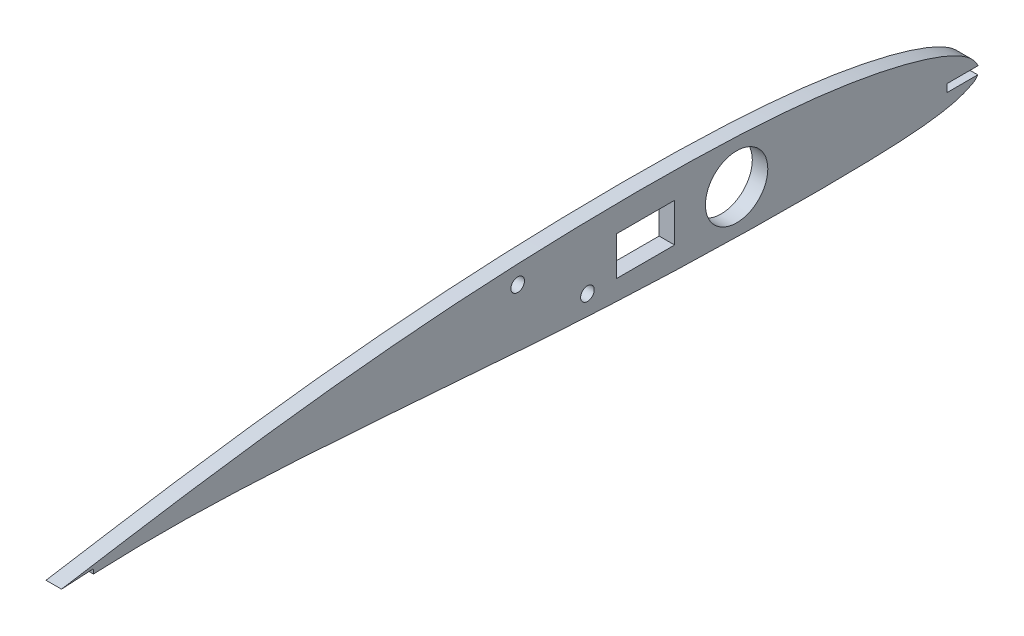
SolidWorks part; units mm, degrees
material "ABS generico"
ref_plane "Piano frontale" through (0, 0, 0) normal (0, 0, 1) x (1, 0, 0)
ref_plane "Piano superiore" through (0, 0, 0) normal (0, 1, 0) x (1, 0, 0)
ref_plane "Piano destro" through (0, 0, 0) normal (1, 0, 0) x (0, 0, -1)
curve "Curva1"
  spline degree 3 poles (0, 0.1724, 248.285) (0, -0.053, 250.4273) (0, 0.2462, 248.3284) (0, 0.5529, 246.6445) (0, 1.2459, 242.6221) (0, 2.0989, 237.7464) (0, 3.1818, 231.3634) (0, 4.2933, 223.9772) (0, 5.7312, 215.5604) (0, 7.1315, 206.3004) (0, 8.6324, 196.1631) (0, 10.1162, 185.3524) (0, 11.5493, 173.9891) (0, 12.8816, 162.1914) (0, 14.0593, 150.0724) (0, 15.0523, 137.7438) (0, 15.8256, 125.3116) (0, 16.3834, 112.8888) (0, 16.7267, 100.597) (0, 16.8648, 88.5669) (0, 16.792, 76.9314) (0, 16.4941, 65.8165) (0, 15.9609, 55.3329) (0, 15.1594, 45.573) (0, 14.0978, 36.6074) (0, 12.7884, 28.4972) (0, 11.2839, 21.2988) (0, 9.6413, 15.0749) (0, 7.9136, 9.8809) (0, 6.1182, 5.7699) (0, 4.2384, 2.7289) (0, 2.3057, 0.8126) (0, 0.7927, 0.0312) (0, -0.4105, -0.0213) (0, -1.7115, 0.4949) (0, -2.8658, 2.6253) (0, -4.0404, 5.6977) (0, -4.9287, 10.0719) (0, -5.5974, 15.6262) (0, -6.0122, 22.4122) (0, -6.265, 30.3619) (0, -6.3814, 39.3972) (0, -6.3554, 49.3987) (0, -6.2185, 60.2453) (0, -5.9476, 71.8018) (0, -5.5368, 83.9408) (0, -4.9386, 96.5461) (0, -4.1527, 109.5201) (0, -3.2196, 122.7671) (0, -2.1909, 136.1764) (0, -1.148, 149.6158) (0, -0.1602, 162.9314) (0, 0.706, 175.9537) (0, 1.3896, 188.4999) (0, 1.8332, 200.3712) (0, 1.9676, 211.3376) (0, 1.8232, 221.1842) (0, 1.4973, 229.6804) (0, 1.0741, 236.8065) (0, 0.6857, 242.1894) (0, 0.3087, 246.5181) (0, 0.1724, 248.285) (0, -0.053, 250.4273) (0, 0.2462, 248.3284) knots -0.014202 -0.006329 -0.001589 0 0.001576 0.006211 0.01368 0.023764 0.036307 0.051658 0.068045 0.086769 0.107053 0.128647 0.151303 0.174786 0.19886 0.223309 0.247929 0.272522 0.296848 0.320648 0.343669 0.365658 0.3864 0.405741 0.423561 0.439779 0.454311 0.467034 0.477831 0.486643 0.493542 0.498786 0.50271 0.50309 0.505896 0.510322 0.516831 0.525521 0.536535 0.549945 0.565696 0.583577 0.603379 0.624844 0.647727 0.671743 0.696673 0.722357 0.748609 0.77521 0.801891 0.828329 0.854175 0.879074 0.902636 0.924421 0.943939 0.960827 0.974827 0.985798 0.993671 0.998411 1 1.001576 1.006211 1.01368 periodic
sketch "Schizzo1" plane through (0, 0, 0) normal (1, 0, 0) x (0, 0, -1)
  line L0 (-250, 0) -> (0.0001, 0.0174) construction
  line L1 (0.0001, 0.0174) -> (-0.0034, 50.0174) construction
  line L2 (-62.4999, 16.3096) -> (-62.4999, -6.155) construction
  line L4 (-78.4999, 10.0773) -> (-93.4999, 10.0773)
  line L5 (-78.4999, 10.0773) -> (-78.4999, 0.0773)
  line L6 (-78.4999, 0.0773) -> (-93.4999, 0.0773)
  line L7 (-93.4999, 10.0773) -> (-93.4999, 0.0773)
  circle A0 centre (-62.4999, 5.0773) radius 8.05
  spline S0 degree 3 poles (-248.3284, 0.2462) (-250.4273, -0.053) (-248.285, 0.1724) (-246.5181, 0.3087) (-242.1894, 0.6857) (-236.8065, 1.0741) (-229.6804, 1.4973) (-221.1842, 1.8232) (-211.3376, 1.9676) (-200.3712, 1.8332) (-188.4999, 1.3896) (-175.9537, 0.706) (-162.9314, -0.1602) (-149.6158, -1.148) (-136.1764, -2.1909) (-122.7671, -3.2196) (-109.5201, -4.1527) (-96.5461, -4.9386) (-83.9408, -5.5368) (-71.8018, -5.9476) (-60.2453, -6.2185) (-49.3987, -6.3554) (-39.3972, -6.3814) (-30.3619, -6.265) (-22.4122, -6.0122) (-15.6262, -5.5974) (-10.0719, -4.9287) (-5.6977, -4.0404) (-2.6253, -2.8658) (-0.4949, -1.7115) (0.0213, -0.4105) (-0.0312, 0.7927) (-0.8126, 2.3057) (-2.7289, 4.2384) (-5.7699, 6.1182) (-9.8809, 7.9136) (-15.0749, 9.6413) (-21.2988, 11.2839) (-28.4972, 12.7884) (-36.6074, 14.0978) (-45.573, 15.1594) (-55.3329, 15.9609) (-65.8165, 16.4941) (-76.9314, 16.792) (-88.5669, 16.8648) (-100.597, 16.7267) (-112.8888, 16.3834) (-125.3116, 15.8256) (-137.7438, 15.0523) (-150.0724, 14.0593) (-162.1914, 12.8816) (-173.9891, 11.5493) (-185.3524, 10.1162) (-196.1631, 8.6324) (-206.3004, 7.1315) (-215.5604, 5.7312) (-223.9772, 4.2933) (-231.3634, 3.1818) (-237.7464, 2.0989) (-242.6221, 1.2459) (-246.6445, 0.5529) (-248.3284, 0.2462) (-250.4273, -0.053) (-248.285, 0.1724) knots -0.01368 -0.006211 -0.001576 0 0.001589 0.006329 0.014202 0.025173 0.039173 0.056061 0.075579 0.097364 0.120926 0.145825 0.171671 0.198109 0.22479 0.251391 0.277643 0.303327 0.328257 0.352273 0.375156 0.396621 0.416423 0.434304 0.450055 0.463465 0.474479 0.483169 0.489678 0.494104 0.49691 0.49729 0.501214 0.506458 0.513357 0.522169 0.532966 0.545689 0.560221 0.576439 0.594259 0.6136 0.634342 0.656331 0.679352 0.703152 0.727478 0.752071 0.776691 0.80114 0.825214 0.848697 0.871353 0.892947 0.913231 0.931955 0.948342 0.963693 0.976236 0.98632 0.993789 0.998424 1 1.001589 1.006329 1.014202 only from (-250, 0) to (-250, 0) construction
  spline S1 degree 3 poles (-248.3284, 0.2462) (-250.4273, -0.053) (-248.285, 0.1724) (-246.5181, 0.3087) (-242.1894, 0.6857) (-236.8065, 1.0741) (-229.6804, 1.4973) (-221.1842, 1.8232) (-211.3376, 1.9676) (-200.3712, 1.8332) (-188.4999, 1.3896) (-175.9537, 0.706) (-162.9314, -0.1602) (-149.6158, -1.148) (-136.1764, -2.1909) (-122.7671, -3.2196) (-109.5201, -4.1527) (-96.5461, -4.9386) (-83.9408, -5.5368) (-71.8018, -5.9476) (-60.2453, -6.2185) (-49.3987, -6.3554) (-39.3972, -6.3814) (-30.3619, -6.265) (-22.4122, -6.0122) (-15.6262, -5.5974) (-10.0719, -4.9287) (-5.6977, -4.0404) (-2.6253, -2.8658) (-0.4949, -1.7115) (0.0213, -0.4105) (-0.0312, 0.7927) (-0.8126, 2.3057) (-2.7289, 4.2384) (-5.7699, 6.1182) (-9.8809, 7.9136) (-15.0749, 9.6413) (-21.2988, 11.2839) (-28.4972, 12.7884) (-36.6074, 14.0978) (-45.573, 15.1594) (-55.3329, 15.9609) (-65.8165, 16.4941) (-76.9314, 16.792) (-88.5669, 16.8648) (-100.597, 16.7267) (-112.8888, 16.3834) (-125.3116, 15.8256) (-137.7438, 15.0523) (-150.0724, 14.0593) (-162.1914, 12.8816) (-173.9891, 11.5493) (-185.3524, 10.1162) (-196.1631, 8.6324) (-206.3004, 7.1315) (-215.5604, 5.7312) (-223.9772, 4.2933) (-231.3634, 3.1818) (-237.7464, 2.0989) (-242.6221, 1.2459) (-246.6445, 0.5529) (-248.3284, 0.2462) (-250.4273, -0.053) (-248.285, 0.1724) knots -0.01368 -0.006211 -0.001576 0 0.001589 0.006329 0.014202 0.025173 0.039173 0.056061 0.075579 0.097364 0.120926 0.145825 0.171671 0.198109 0.22479 0.251391 0.277643 0.303327 0.328257 0.352273 0.375156 0.396621 0.416423 0.434304 0.450055 0.463465 0.474479 0.483169 0.489678 0.494104 0.49691 0.49729 0.501214 0.506458 0.513357 0.522169 0.532966 0.545689 0.560221 0.576439 0.594259 0.6136 0.634342 0.656331 0.679352 0.703152 0.727478 0.752071 0.776691 0.80114 0.825214 0.848697 0.871353 0.892947 0.913231 0.931955 0.948342 0.963693 0.976236 0.98632 0.993789 0.998424 1 1.001589 1.006329 1.014202 only from (-250, 0) to (-250, 0)
  point P11 (-78.4999, 5.0773)
  dimension "D3" = 16.1
  dimension "D1" = 50
  dimension "D2" = 62.5
  dimension "D4" = 15
  dimension "D5" = 10
  dimension "D6" = 16
extrude "CorpoFoam" add sketch "Schizzo1" along normal blind 4
sketch "Schizzo2" plane through (0, 0, 0) normal (-1, 0, 0) x (0, 0, 1)
  line L0 (0, 0) -> (62.4999, 5.0773) construction
  line L9 (-0.0001, 1) -> (8.1999, 1)
  line L13 (-0.0001, 1) -> (-0.0001, -1)
  line L14 (-0.0001, -1) -> (8.1999, -1)
  line L15 (8.1999, 1) -> (8.1999, -1)
  spline S1 degree 3 poles (248.285, 0.1724) (250.4273, -0.053) (248.3284, 0.2462) (246.6445, 0.5529) (242.6221, 1.2459) (237.7464, 2.0989) (231.3634, 3.1818) (223.9772, 4.2933) (215.5604, 5.7312) (206.3004, 7.1315) (196.1631, 8.6324) (185.3524, 10.1162) (173.9891, 11.5493) (162.1914, 12.8816) (150.0724, 14.0593) (137.7438, 15.0523) (125.3116, 15.8256) (112.8888, 16.3834) (100.597, 16.7267) (88.5669, 16.8648) (76.9314, 16.792) (65.8165, 16.4941) (55.3329, 15.9609) (45.573, 15.1594) (36.6074, 14.0978) (28.4972, 12.7884) (21.2988, 11.2839) (15.0749, 9.6413) (9.8809, 7.9136) (5.7699, 6.1182) (2.7289, 4.2384) (0.8126, 2.3057) (0.0312, 0.7927) (-0.0213, -0.4105) (0.4949, -1.7115) (2.6253, -2.8658) (5.6977, -4.0404) (10.0719, -4.9287) (15.6262, -5.5974) (22.4122, -6.0122) (30.3619, -6.265) (39.3972, -6.3814) (49.3987, -6.3554) (60.2453, -6.2185) (71.8018, -5.9476) (83.9408, -5.5368) (96.5461, -4.9386) (109.5201, -4.1527) (122.7671, -3.2196) (136.1764, -2.1909) (149.6158, -1.148) (162.9314, -0.1602) (175.9537, 0.706) (188.4999, 1.3896) (200.3712, 1.8332) (211.3376, 1.9676) (221.1842, 1.8232) (229.6804, 1.4973) (236.8065, 1.0741) (242.1894, 0.6857) (246.5181, 0.3087) (248.285, 0.1724) (250.4273, -0.053) (248.3284, 0.2462) knots -0.014202 -0.006329 -0.001589 0 0.001576 0.006211 0.01368 0.023764 0.036307 0.051658 0.068045 0.086769 0.107053 0.128647 0.151303 0.174786 0.19886 0.223309 0.247929 0.272522 0.296848 0.320648 0.343669 0.365658 0.3864 0.405741 0.423561 0.439779 0.454311 0.467034 0.477831 0.486643 0.493542 0.498786 0.50271 0.50309 0.505896 0.510322 0.516831 0.525521 0.536535 0.549945 0.565696 0.583577 0.603379 0.624844 0.647727 0.671743 0.696673 0.722357 0.748609 0.77521 0.801891 0.828329 0.854175 0.879074 0.902636 0.924421 0.943939 0.960827 0.974827 0.985798 0.993671 0.998411 1 1.001576 1.006211 1.01368 only from (250, 0) to (250, 0) construction
  point P6 (-0.0001, 0)
  dimension "D1" = 2
  dimension "D2" = 8.2
extrude "IntagliFrontali" cut sketch "Schizzo2" against normal through all
sketch "Schizzo3" plane through (0, 0, 0) normal (-1, 0, 0) x (0, 0, 1)
  line L0 (98.4999, 13.9643) -> (98.4999, 16.7316) construction
  line L1 (98.4999, 13.9643) -> (121.4999, 13.9643) construction
  line L2 (98.4999, 13.9643) -> (98.4999, -2.0357) construction
  line L3 (98.4999, -2.0357) -> (121.4999, -2.0357) construction
  line L4 (121.4999, 13.9643) -> (121.4999, -2.0357) construction
  line L5 (98.4999, -2.0357) -> (98.4999, -4.803) construction
  line L6 (93.4999, 10.0773) -> (93.4999, 0.0773) construction
  line L7 (98.4999, -2.0357) -> (100.9999, 0.4643) construction
  line L8 (100.9999, 0.4643) -> (118.9999, 11.4643) construction
  line L9 (118.9999, 11.4643) -> (121.4999, 13.9643) construction
  circle A0 centre (100.9999, 0.4643) radius 1.75
  circle A1 centre (118.9999, 11.4643) radius 1.75
  spline S0 degree 3 poles (0.2015, 1) (0.3423, 1.3625) (1.0086, 2.5034) (2.7289, 4.2384) (5.7699, 6.1182) (9.8809, 7.9136) (15.0749, 9.6413) (21.2988, 11.2839) (28.4972, 12.7884) (36.6074, 14.0978) (45.573, 15.1594) (55.3329, 15.9609) (65.8165, 16.4941) (76.9314, 16.792) (88.5669, 16.8648) (100.597, 16.7267) (112.8888, 16.3834) (125.3116, 15.8256) (137.7438, 15.0523) (150.0724, 14.0593) (162.1914, 12.8816) (173.9891, 11.5493) (185.3524, 10.1162) (196.1631, 8.6324) (206.3004, 7.1315) (215.5604, 5.7312) (223.9772, 4.2933) (231.3634, 3.1818) (237.7464, 2.0989) (242.6221, 1.2459) (246.6445, 0.5529) (248.3284, 0.2462) (250.4273, -0.053) (248.285, 0.1724) (246.5181, 0.3087) (242.1894, 0.6857) (236.8065, 1.0741) (229.6804, 1.4973) (221.1842, 1.8232) (211.3376, 1.9676) (200.3712, 1.8332) (188.4999, 1.3896) (175.9537, 0.706) (162.9314, -0.1602) (149.6158, -1.148) (136.1764, -2.1909) (122.7671, -3.2196) (109.5201, -4.1527) (96.5461, -4.9386) (83.9408, -5.5368) (71.8018, -5.9476) (60.2453, -6.2185) (49.3987, -6.3554) (39.3972, -6.3814) (30.3619, -6.265) (22.4122, -6.0122) (15.6262, -5.5974) (10.0719, -4.9287) (5.6977, -4.0404) (2.6253, -2.8658) (0.8093, -1.8819) (0.3291, -1.1192) (0.2665, -1) knots 0.498933 0.498933 0.498933 0.498933 0.501214 0.506458 0.513357 0.522169 0.532966 0.545689 0.560221 0.576439 0.594259 0.6136 0.634342 0.656331 0.679352 0.703152 0.727478 0.752071 0.776691 0.80114 0.825214 0.848697 0.871353 0.892947 0.913231 0.931955 0.948342 0.963693 0.976236 0.98632 0.993789 0.998424 1 1.001589 1.006329 1.014202 1.025173 1.039173 1.056061 1.075579 1.097364 1.120926 1.145825 1.171671 1.198109 1.22479 1.251391 1.277643 1.303327 1.328257 1.352273 1.375156 1.396621 1.416423 1.434304 1.450055 1.463465 1.474479 1.483169 1.489678 1.494104 1.494882 1.494882 1.494882 1.494882 construction
  dimension "D4" = 3.5
  dimension "D1" = 23
  dimension "D2" = 16
  dimension "D3" = 5
  dimension "D5" = 2.5
  dimension "D6" = 2.5
  dimension "D7" = 45
extrude "ForiTrasduttorePitot" cut sketch "Schizzo3" against normal through all
sketch "Schizzo4" plane through (0, 0, 0) normal (-1, 0, 0) x (0, 0, 1)
  line L0 (228.544, 2.7244) -> (228.4772, 1.5262)
  line L1 (228.4772, 1.5262) -> (236.6645, 1.07)
  line L2 (236.6645, 1.07) -> (236.7313, 2.2681)
  line L3 (236.7313, 2.2681) -> (228.544, 2.7244)
  line L4 (237.191, 10.5177) -> (236.2665, -6.0737)
  line L5 (236.2665, -6.0737) -> (255.0429, -7.12)
  line L6 (255.0429, -7.12) -> (255.9674, 9.4715)
  line L7 (255.9674, 9.4715) -> (237.191, 10.5177)
  spline S0 degree 3 poles (0.2015, 1) (0.3423, 1.3625) (1.0086, 2.5034) (2.7289, 4.2384) (5.7699, 6.1182) (9.8809, 7.9136) (15.0749, 9.6413) (21.2988, 11.2839) (28.4972, 12.7884) (36.6074, 14.0978) (45.573, 15.1594) (55.3329, 15.9609) (65.8165, 16.4941) (76.9314, 16.792) (88.5669, 16.8648) (100.597, 16.7267) (112.8888, 16.3834) (125.3116, 15.8256) (137.7438, 15.0523) (150.0724, 14.0593) (162.1914, 12.8816) (173.9891, 11.5493) (185.3524, 10.1162) (196.1631, 8.6324) (206.3004, 7.1315) (215.5604, 5.7312) (223.9772, 4.2933) (231.3634, 3.1818) (237.7464, 2.0989) (242.6221, 1.2459) (246.6445, 0.5529) (248.3284, 0.2462) (250.4273, -0.053) (248.285, 0.1724) (246.5181, 0.3087) (242.1894, 0.6857) (236.8065, 1.0741) (229.6804, 1.4973) (221.1842, 1.8232) (211.3376, 1.9676) (200.3712, 1.8332) (188.4999, 1.3896) (175.9537, 0.706) (162.9314, -0.1602) (149.6158, -1.148) (136.1764, -2.1909) (122.7671, -3.2196) (109.5201, -4.1527) (96.5461, -4.9386) (83.9408, -5.5368) (71.8018, -5.9476) (60.2453, -6.2185) (49.3987, -6.3554) (39.3972, -6.3814) (30.3619, -6.265) (22.4122, -6.0122) (15.6262, -5.5974) (10.0719, -4.9287) (5.6977, -4.0404) (2.6253, -2.8658) (0.8093, -1.8819) (0.3291, -1.1192) (0.2665, -1) knots 0.498933 0.498933 0.498933 0.498933 0.501214 0.506458 0.513357 0.522169 0.532966 0.545689 0.560221 0.576439 0.594259 0.6136 0.634342 0.656331 0.679352 0.703152 0.727478 0.752071 0.776691 0.80114 0.825214 0.848697 0.871353 0.892947 0.913231 0.931955 0.948342 0.963693 0.976236 0.98632 0.993789 0.998424 1 1.001589 1.006329 1.014202 1.025173 1.039173 1.056061 1.075579 1.097364 1.120926 1.145825 1.171671 1.198109 1.22479 1.251391 1.277643 1.303327 1.328257 1.352273 1.375156 1.396621 1.416423 1.434304 1.450055 1.463465 1.474479 1.483169 1.489678 1.494104 1.494882 1.494882 1.494882 1.494882 construction
  spline M14 degree 3 poles (248.285, 0.1724) (250.4273, -0.053) (248.3284, 0.2462) (246.6445, 0.5529) (242.6221, 1.2459) (237.7464, 2.0989) (231.3634, 3.1818) (223.9772, 4.2933) (215.5604, 5.7312) (206.3004, 7.1315) (196.1631, 8.6324) (185.3524, 10.1162) (173.9891, 11.5493) (162.1914, 12.8816) (150.0724, 14.0593) (137.7438, 15.0523) (125.3116, 15.8256) (112.8888, 16.3834) (100.597, 16.7267) (88.5669, 16.8648) (76.9314, 16.792) (65.8165, 16.4941) (55.3329, 15.9609) (45.573, 15.1594) (36.6074, 14.0978) (28.4972, 12.7884) (21.2988, 11.2839) (15.0749, 9.6413) (9.8809, 7.9136) (5.7699, 6.1182) (2.7289, 4.2384) (0.8126, 2.3057) (0.0312, 0.7927) (-0.0213, -0.4105) (0.4949, -1.7115) (2.6253, -2.8658) (5.6977, -4.0404) (10.0719, -4.9287) (15.6262, -5.5974) (22.4122, -6.0122) (30.3619, -6.265) (39.3972, -6.3814) (49.3987, -6.3554) (60.2453, -6.2185) (71.8018, -5.9476) (83.9408, -5.5368) (96.5461, -4.9386) (109.5201, -4.1527) (122.7671, -3.2196) (136.1764, -2.1909) (149.6158, -1.148) (162.9314, -0.1602) (175.9537, 0.706) (188.4999, 1.3896) (200.3712, 1.8332) (211.3376, 1.9676) (221.1842, 1.8232) (229.6804, 1.4973) (236.8065, 1.0741) (242.1894, 0.6857) (246.5181, 0.3087) (248.285, 0.1724) (250.4273, -0.053) (248.3284, 0.2462) knots -0.014202 -0.006329 -0.001589 0 0.001576 0.006211 0.01368 0.023764 0.036307 0.051658 0.068045 0.086769 0.107053 0.128647 0.151303 0.174786 0.19886 0.223309 0.247929 0.272522 0.296848 0.320648 0.343669 0.365658 0.3864 0.405741 0.423561 0.439779 0.454311 0.467034 0.477831 0.486643 0.493542 0.498786 0.50271 0.50309 0.505896 0.510322 0.516831 0.525521 0.536535 0.549945 0.565696 0.583577 0.603379 0.624844 0.647727 0.671743 0.696673 0.722357 0.748609 0.77521 0.801891 0.828329 0.854175 0.879074 0.902636 0.924421 0.943939 0.960827 0.974827 0.985798 0.993671 0.998411 1 1.001576 1.006211 1.01368 only from (0.2665, -1) to (0.2015, 1)
  dimension "D1" = 1.2
  dimension "D2" = 8.2
  dimension "D3" = 18.7764
  dimension "D4" = 16.5914
  dimension "D5" = 10.8826
extrude "IntaglioPosteriore" cut sketch "Schizzo4" against normal through all contours L6 L7 L4 L5 M14 | L2 M14 | L2 L3 L0 M14
